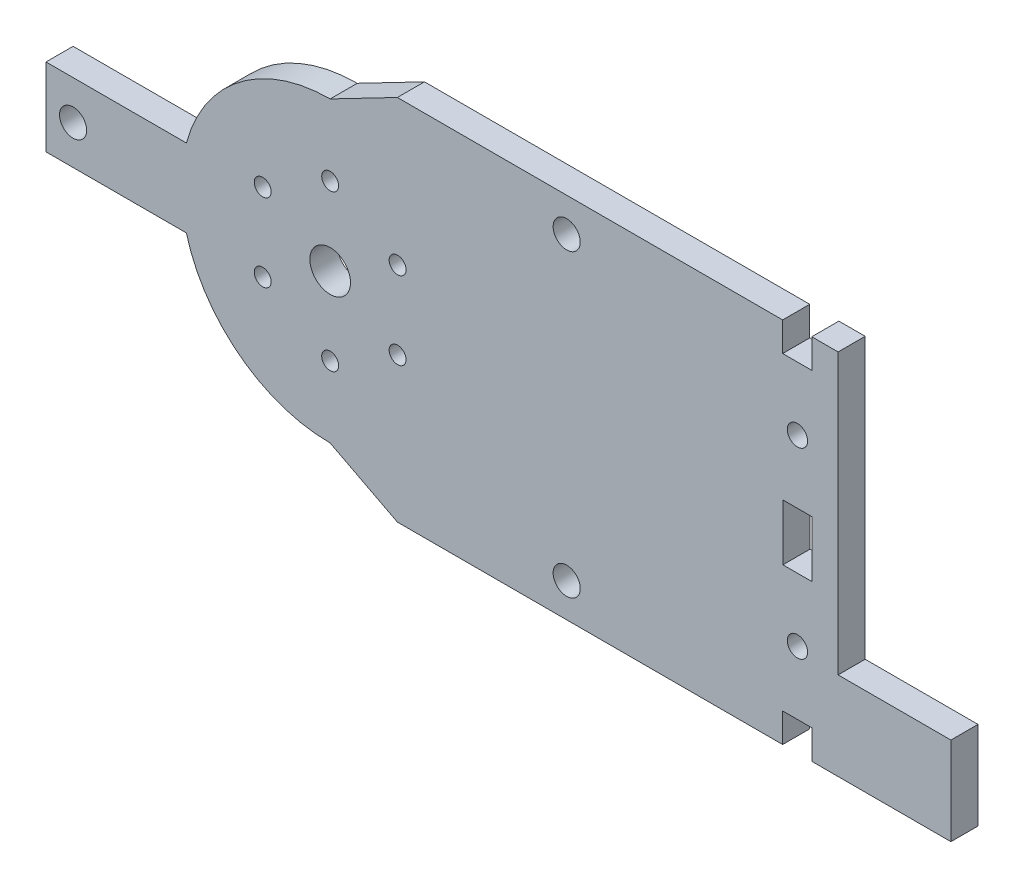
SolidWorks part; units mm, degrees
ref_plane "前视基准面" through (0, 0, 0) normal (0, 0, 1) x (1, 0, 0)
ref_plane "上视基准面" through (0, 0, 0) normal (0, 1, 0) x (1, 0, 0)
ref_plane "右视基准面" through (0, 0, 0) normal (1, 0, 0) x (0, 0, -1)
sketch "草图1" plane through (0, 0, 0) normal (0, 0, 1) x (1, 0, 0)
  line L0 (30.001, 15) -> (30.001, 12) construction
  line L1 (27.8157, 27.15) -> (32.1157, 27.15) construction
  line L2 (32.151, -4.15) -> (27.851, -4.15)
  line L3 (32.151, -4.15) -> (32.151, 4.15)
  line L4 (32.151, 4.15) -> (27.851, 4.15)
  line L5 (27.851, -4.15) -> (27.851, 4.15)
  line L6 (32.151, -4.15) -> (27.851, 4.15) construction
  line L7 (32.151, 4.15) -> (27.851, -4.15) construction
  line L8 (32.1157, 27.15) -> (32.1157, 22.85)
  line L9 (27.8157, 22.85) -> (32.1157, 22.85)
  line L10 (27.8157, 27.15) -> (27.8157, 22.85)
  line L11 (30.001, 0) -> (30.8707, 0) construction
  line L12 (27.8157, -27.15) -> (32.1157, -27.15) construction
  line L13 (30.001, -15) -> (30.001, -12) construction
  line L14 (27.8157, -27.15) -> (27.8157, -22.85)
  line L15 (27.8157, -22.85) -> (32.1157, -22.85)
  line L16 (32.1157, -27.15) -> (32.1157, -22.85)
  line L17 (32.1157, -27.15) -> (36.001, -27.15)
  line L18 (36.001, -27.15) -> (36.001, 27.15) construction
  line L19 (36.001, 27.15) -> (32.1157, 27.15)
  line L23 (-38.999, -22.002) -> (-29.075, -27.15)
  line L25 (-38.999, 22.002) -> (-29.075, 27.15)
  line L29 (27.8157, -27.15) -> (-29.075, -27.15)
  line L30 (-29.075, 27.15) -> (27.8157, 27.15)
  line L31 (-29.075, -27.15) -> (-29.075, 27.15) construction
  line L34 (-48.9583, 5.75) -> (-48.9583, -5.75) construction
  line L38 (-60.2364, 5.75) -> (-80.9583, 5.75)
  line L39 (-80.9583, -5.75) -> (-60.2364, -5.75)
  line L40 (-80.9583, 5.75) -> (-80.9583, -5.75)
  line L41 (36.001, -27.15) -> (52.6592, -27.15)
  line L42 (52.6592, -27.15) -> (52.6592, -14.15)
  line L43 (52.6592, -14.15) -> (36.001, -14.15)
  line L44 (36.001, -14.15) -> (36.001, 27.15)
  circle A0 centre (30.001, 13.5) radius 1.5
  circle A1 centre (30.001, -13.5) radius 1.5
  circle A3 centre (-38.999, 0) radius 3
  circle A6 centre (-38.999, 0) radius 11.5 construction
  circle A7 centre (-38.999, -11.5) radius 1.25
  circle A18 centre (-38.999, 0) radius 22.002 construction
  circle A25 centre (-48.9583, -5.75) radius 1.25
  circle A26 centre (-48.9583, 5.75) radius 1.25
  circle A27 centre (-38.999, 11.5) radius 1.25
  circle A28 centre (-29.0397, 5.75) radius 1.25
  circle A29 centre (-29.0397, -5.75) radius 1.25
  circle A30 centre (-4.075, -22.15) radius 2
  circle A31 centre (-4.075, 22.15) radius 2
  arc A32 (-38.999, -22.002) -> (-60.2364, -5.75) centre (-38.999, 0) cw
  arc A33 (-60.2364, 5.75) -> (-38.999, 22.002) centre (-38.999, 0) cw
  circle A34 centre (-76.9583, 0) radius 2
  point P4 (30.001, 0)
  dimension "D3" = 6
  dimension "D4" = 75
  dimension "D5" = 6
  dimension "D6" = 11.5
  dimension "D7" = 23
  dimension "D8" = 2.5
  dimension "D9" = 25
  dimension "D11" = 5
  dimension "D14" = 4
  dimension "D1" = 8.3
  dimension "D2" = 4.3
  dimension "D10" = 5
  dimension "D12" = 25
  dimension "D13" = 28
  dimension "D15" = 3.8853
  dimension "D16" = 4.3
  dimension "D17" = 13
extrude "凸台-拉伸1" add sketch "草图1" along normal blind 4
